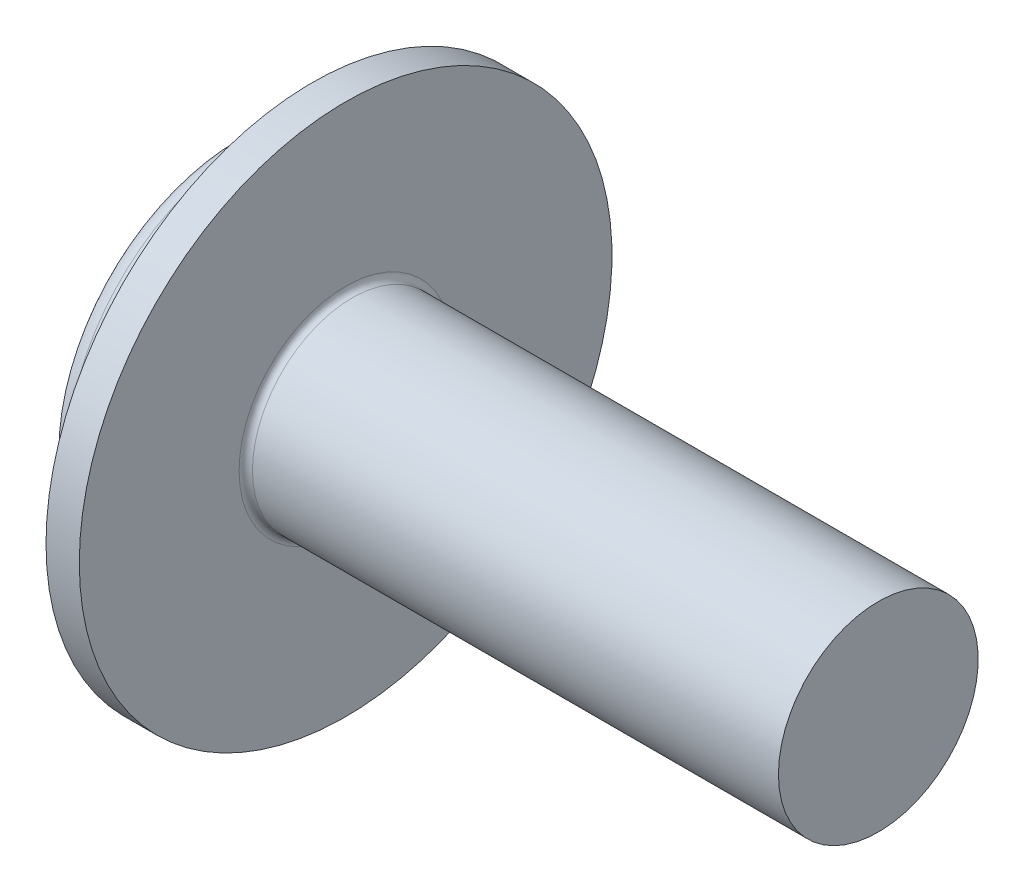
SolidWorks part; units mm, degrees
ref_plane "Plane1" through (0, 0, 0) normal (0, 0, 1) x (1, 0, 0)
ref_plane "Plane2" through (0, 0, 0) normal (0, 1, 0) x (1, 0, 0)
ref_plane "Plane3" through (0, 0, 0) normal (1, 0, 0) x (0, 0, -1)
sketch "BodySke" plane through (0, 0, 0) normal (0, 0, 1) x (1, 0, 0)
  line L0 (2.4, 1.5) -> (2.4, 2.8)
  line L1 (2.65, 6.35) -> (2.65, -3.175) construction
  line L2 (-25.4, 0) -> (127, 0) construction
  line L3 (10.4, 0) -> (0, 0)
  line L4 (2.4, 1.5) -> (10.4, 1.5)
  line L5 (10.4, 1.5) -> (10.4, 0)
  line L6 (1.0035, 2.8) -> (2.4, 2.8)
  line L8 (2.4, 6.35) -> (2.4, -3.175) construction
  arc A0 (0.7754, 2.6744) -> (0, 0) centre (5, 0) ccw
  arc A2 (0.7754, 2.6744) -> (1.0035, 2.8) centre (1.0035, 2.53) cw
  dimension "Head_crown_rad" = 5
  dimension "Head_fillet_rad" = 0.27
  dimension "Length" = 8
  dimension "Head_ht" = 2.4
  dimension "Head_dia" = 5.6
  dimension "Advance" = 0.5
  dimension "Thread_nom" = 8
  dimension "Diameter" = 3
revolve "Base-Revolve" add sketch "BodySke"
cosmetic thread "ThreadCosmetic" [suppressed]
fillet "Fillet1" radius 0.1 1 edges at (2.4, 0, 1.5)
sketch "Sketch3" plane through (0, 0, 0) normal (1, 0, 0) x (0, 0, -1)
  line L0 (0.37, -1.4) -> (-0.37, -1.4)
  line L1 (0.37, -1.4) -> (0.37, 1.4)
  line L2 (-0.37, 1.4) -> (0.37, 1.4)
  line L3 (-0.37, 1.4) -> (-0.37, -1.4)
  dimension "Cross_dia" = 2.8
  dimension "D1" = 1.4
  dimension "Cross_width" = 0.74
  dimension "D2" = 0.37
ref_plane "Plane4" through (1.75, 0, 0) normal (1, 0, 0) x (0, 0, -1)
sketch "Sketch4" plane through (1.75, 0, 0) normal (1, 0, 0) x (0, 0, -1)
  line L0 (0.37, -0.5275) -> (-0.37, -0.5275)
  line L1 (0.37, -0.5275) -> (0.37, 0.5275)
  line L2 (-0.37, 0.5275) -> (0.37, 0.5275)
  line L3 (-0.37, 0.5275) -> (-0.37, -0.5275)
  dimension "D1" = 0.74
  dimension "D2" = 1.055
  dimension "D3" = 0.37
  dimension "D4" = 0.5275
loft "Recess" cut profiles "Sketch3", "Sketch4"
pattern_circular "RecPat" count 2 every 90 about axis through (0, 0, 0) along (1, 0, 0) of "Recess"
sketch "RecCorSke" plane through (0, 0, 0) normal (0, 0, 1) x (1, 0, 0)
  line L0 (-3.175, 0) -> (15.875, 0) construction
  line L1 (-25.4, 0) -> (127, 0) construction
  line L2 (0, 0) -> (0, 0.6784)
  line L3 (0, 0.6784) -> (1.75, 0.556)
  line L4 (1.75, 0.556) -> (1.9307, 0)
  line L5 (1.9307, 0) -> (0, 0)
  dimension "Diameter" = 1.112
  dimension "Depth" = 1.75
  dimension "Draft_angle" = 4
  dimension "Bottom_angle" = 18
revolve "RecessCore" cut sketch "RecCorSke" angle 360 about L0
sketch "ThdSchSke" plane through (0, 0, 0) normal (0, 0, 1) x (1, 0, 0)
  line L0 (3.4, -1.2195) -> (3.2036, -1.5)
  line L1 (3.4, -1.2195) -> (3.5964, -1.5)
  line L2 (3.5964, -1.5) -> (3.5964, -1.875)
  line L3 (-3.175, 0) -> (5.1513, 0) construction
  line L5 (3.5964, -1.875) -> (3.2036, -1.875)
  line L6 (3.2036, -1.875) -> (3.2036, -1.5)
  dimension "Diameter" = 3
  dimension "SideAngle" = 55
  dimension "VeeAngle" = 70
  dimension "Thread_minor" = 2.439
  dimension "Overcut" = 3.75
  dimension "Start" = 3.4
revolve "ThreadSchematic" [suppressed] cut sketch "ThdSchSke" angle 360 about L3
pattern_linear "ThdSchPat" [suppressed]
sketch "Schizzo1" plane through (0, 0, 0) normal (0, 1, 0) x (1, 0, 0)
  line L5 (0, 0) -> (10.4, 0) construction
  line L6 (10.4, -1.5) -> (10.4, 1.5) construction
  line L8 (2.4, -2.8) -> (2.4, 2.8) construction
  line L9 (2.4, 0) -> (1.9, 0)
  line L10 (2.4, 0) -> (2.4, -4)
  line L11 (2.4, -4) -> (1.9, -4)
  line L12 (1.9, 0) -> (1.9, -4)
  dimension "D1" = 0.5
  dimension "D2" = 4
revolve "Rivoluzione2" add sketch "Schizzo1" angle 360 about L5
equation "\"D1@Sketch3\" = \"Cross_dia@Sketch3\" / 2"
equation "\"D2@Sketch3\" = \"Cross_width@Sketch3\" / 2"
equation "\"Depth@RecCorSke\" = \"Cross_depth@Plane4\""
equation "\"D1@Sketch4\" = \"Cross_width@Sketch3\""
equation "\"D2@Sketch4\" = \"Cross_dia@Sketch3\" - 2.0 * \"Cross_depth@Plane4\" * tan(26.5  * 0.017453292)"
equation "\"D3@Sketch4\" = \"D1@Sketch4\" / 2"
equation "\"D4@Sketch4\" = \"D2@Sketch4\" / 2"
equation "\"Thread_length@ThreadCosmetic\" = ((sgn( (\"Length@BodySke\" - \"Advance@BodySke\" * 2.0 ) - \"Thread_nom@BodySke\" )-1)*( (\"Length@BodySke\" - \"Advance@BodySke\" * 2.0 ) - \"Thread_nom@BodySke\" ))/-2+ \"Thread_nom@BodySke\""
equation "\"Thread_minor@ThdSchSke\" = \"Thread_minor@ThreadCosmetic\""
equation "\"Diameter@ThdSchSke\" = \"Diameter@BodySke\""
equation "\"Overcut@ThdSchSke\" = \"Diameter@BodySke\" * 1.25"
equation "\"Start@ThdSchSke\" = \"Head_ht@BodySke\" + \"Length@BodySke\" - \"Thread_length@ThreadCosmetic\"  '---Non-countersunk---"
equation "\"Num_threads@ThdSchPat\" = int( \"Thread_length@ThreadCosmetic\" / \"Advance@BodySke\" + 0.999 )  + 1"
equation "\"Advance@ThdSchPat\" = \"Thread_length@ThreadCosmetic\" /  (\"Num_threads@ThdSchPat\" - 1) 'relax it"
